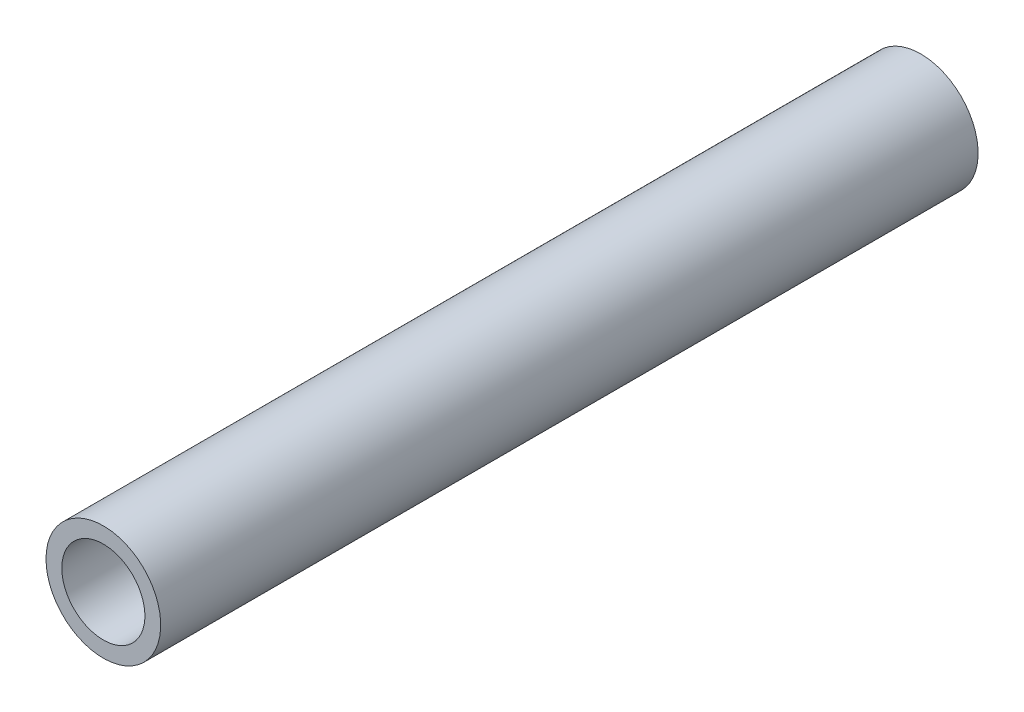
SolidWorks part; units mm, degrees
ref_plane "Front Plane" through (0, 0, 0) normal (0, 0, 1) x (1, 0, 0)
ref_plane "Top Plane" through (0, 0, 0) normal (0, 1, 0) x (1, 0, 0)
ref_plane "Right Plane" through (0, 0, 0) normal (1, 0, 0) x (0, 0, -1)
sketch "Sketch1" plane through (0, 0, 0) normal (0, 0, 1) x (1, 0, 0)
  circle A0 centre (0, 0) radius 10.6934
  circle A1 centre (0, 0) radius 7.747
  dimension "D1" = 21.3868
  dimension "D2" = 15.494
extrude "Boss-Extrude1" add sketch "Sketch1" along normal blind 152.4
